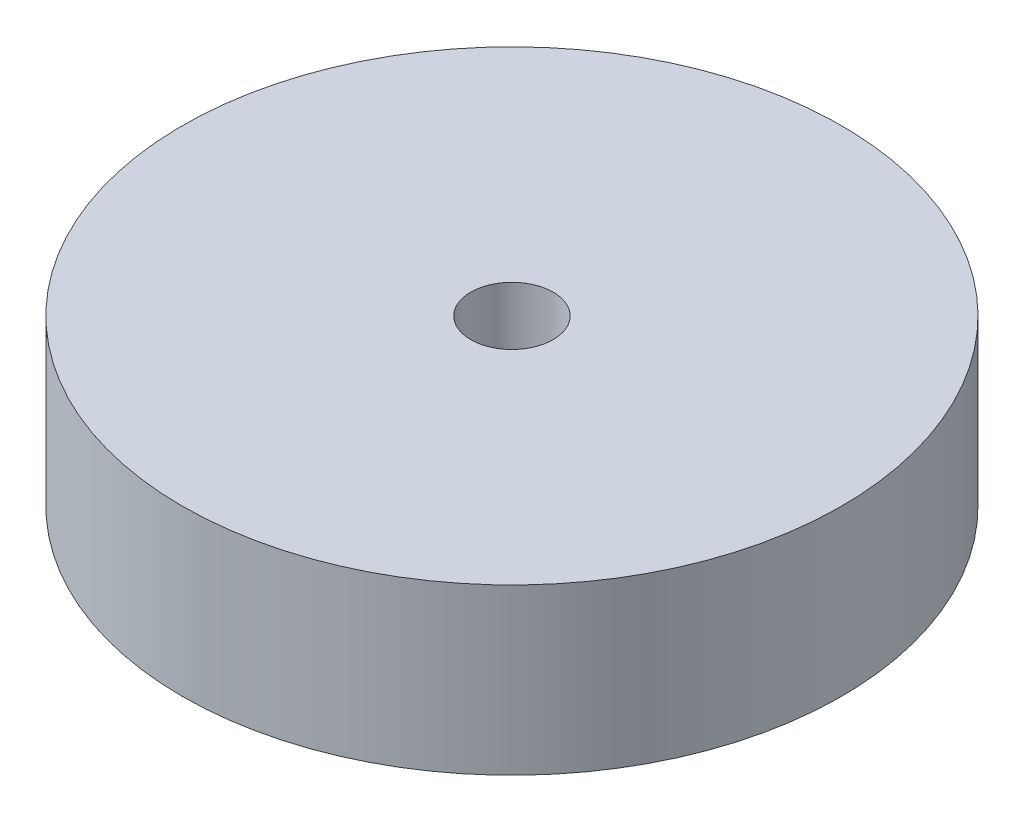
SolidWorks part; units mm, degrees
ref_plane "Front Plane" through (0, 0, 0) normal (0, 0, 1) x (1, 0, 0)
ref_plane "Top Plane" through (0, 0, 0) normal (0, 1, 0) x (1, 0, 0)
ref_plane "Right Plane" through (0, 0, 0) normal (1, 0, 0) x (0, 0, -1)
sketch "Sketch1" plane through (0, 0, 0) normal (0, 1, 0) x (1, 0, 0)
  circle A0 centre (0, 0) radius 101.6
  circle A1 centre (0, 0) radius 12.7
  dimension "D1" = 203.2
  dimension "D2" = 25.4
extrude "Boss-Extrude1" add sketch "Sketch1" along normal blind 50.8
